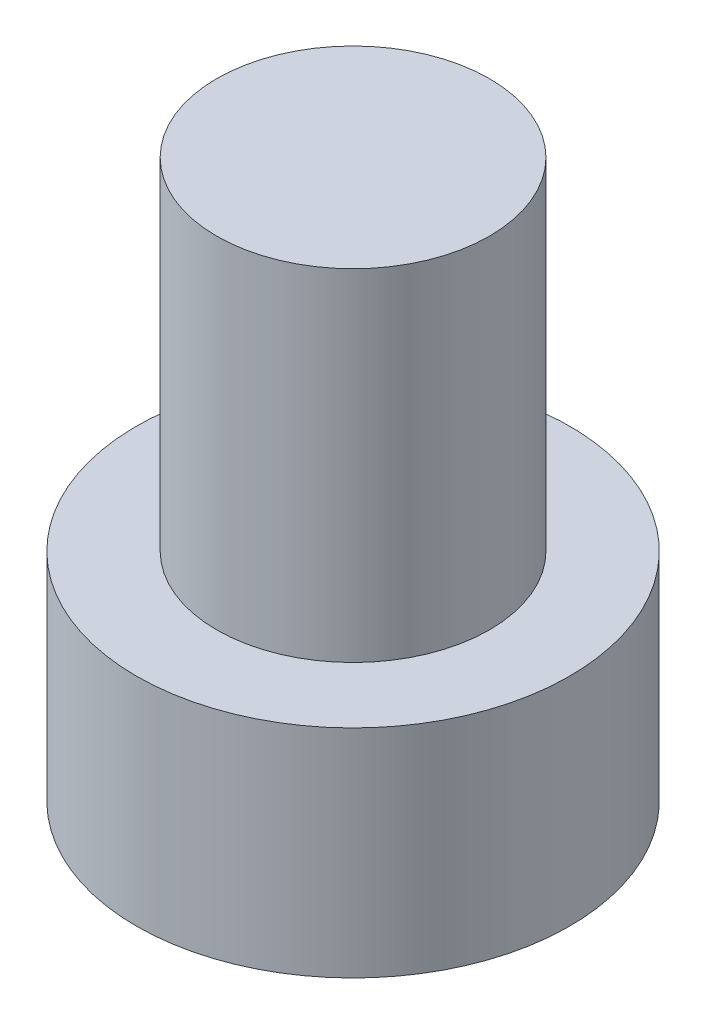
SolidWorks part; units mm, degrees
ref_plane "Front Plane" through (0, 0, 0) normal (0, 0, 1) x (1, 0, 0)
ref_plane "Top Plane" through (0, 0, 0) normal (0, 1, 0) x (1, 0, 0)
ref_plane "Right Plane" through (0, 0, 0) normal (1, 0, 0) x (0, 0, -1)
sketch "Sketch1" plane through (0, 0, 0) normal (0, 1, 0) x (1, 0, 0)
  circle A0 centre (0, 0) radius 3.175
  dimension "D1" = 6.35
extrude "Boss-Extrude1" add sketch "Sketch1" along normal blind 3.175
sketch "Sketch2" plane through (0, 3.175, 0) normal (0, 1, 0) x (1, 0, 0)
  circle A0 centre (0, 0) radius 2
  dimension "D1" = 4
extrude "Boss-Extrude2" add sketch "Sketch2" along normal blind 5
